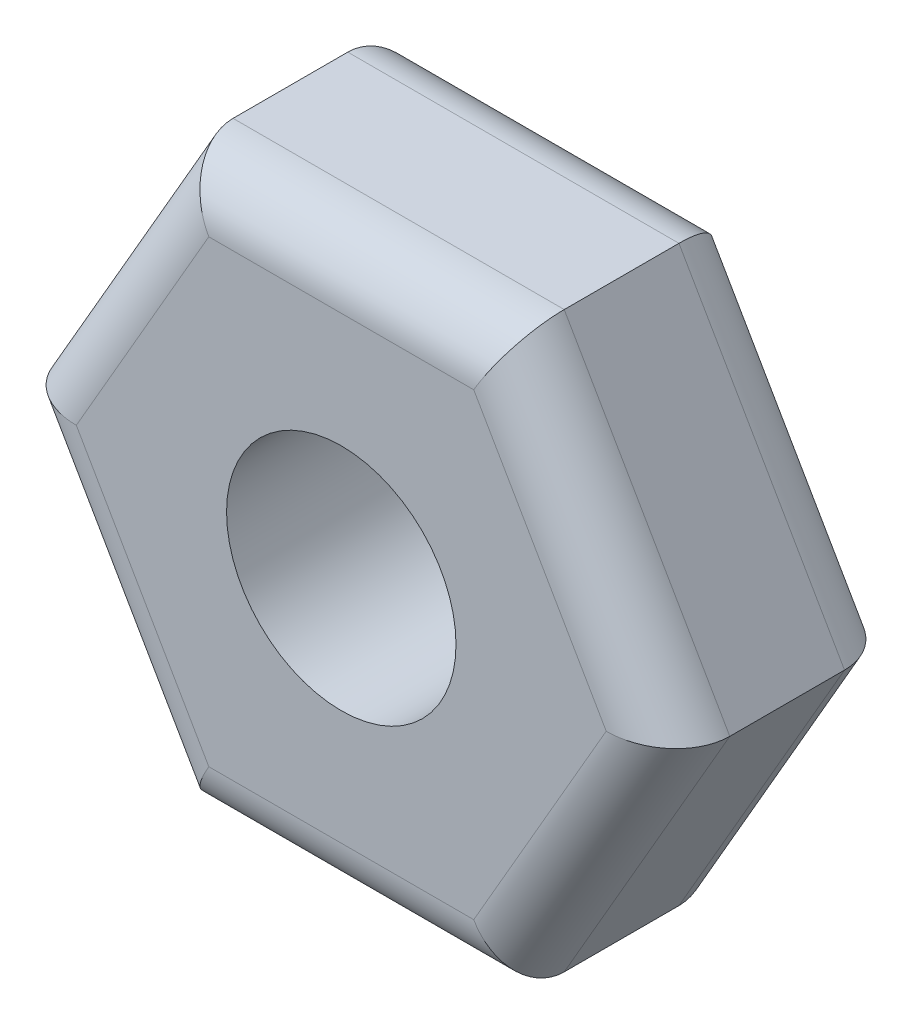
SolidWorks part; units mm, degrees
ref_plane "Alzado" through (0, 0, 0) normal (0, 0, 1) x (1, 0, 0)
ref_plane "Planta" through (0, 0, 0) normal (0, 1, 0) x (1, 0, 0)
ref_plane "Vista lateral" through (0, 0, 0) normal (1, 0, 0) x (0, 0, -1)
sketch "Croquis1" plane through (0, 0, 0) normal (0, 0, 1) x (1, 0, 0)
  line L1 (5.7735, 0) -> (2.8868, 5)
  line L2 (2.8868, 5) -> (-2.8868, 5)
  line L3 (-2.8868, 5) -> (-5.7735, 0)
  line L4 (-5.7735, 0) -> (-2.8868, -5)
  line L5 (-2.8868, -5) -> (2.8868, -5)
  line L6 (2.8868, -5) -> (5.7735, 0)
  circle A0 centre (0, 0) radius 5 construction
  circle A1 centre (0, 0) radius 2
  point P10 (0, 0)
  point P11 (-5.6945, -0.9521)
  point P12 (-5.7735, 0)
  point P13 (-5.7735, 0)
  dimension "D1" = 4
  dimension "D2" = 10
  dimension "D3" = 2.8868
extrude "Saliente-Extruir1" add sketch "Croquis1" along normal blind 4
fillet "Redondeo2" radius 1 6 edges at (4.3301, -2.5, 4) (0, -5, 4) (-4.3301, -2.5, 4) (-4.3301, 2.5, 4) (0, 5, 4) (4.3301, 2.5, 4)
fillet "Redondeo3" radius 1 6 edges at (0, 5, 0) (-4.3301, 2.5, 0) (-4.3301, -2.5, 0) (0, -5, 0) (4.3301, -2.5, 0) (4.3301, 2.5, 0)
